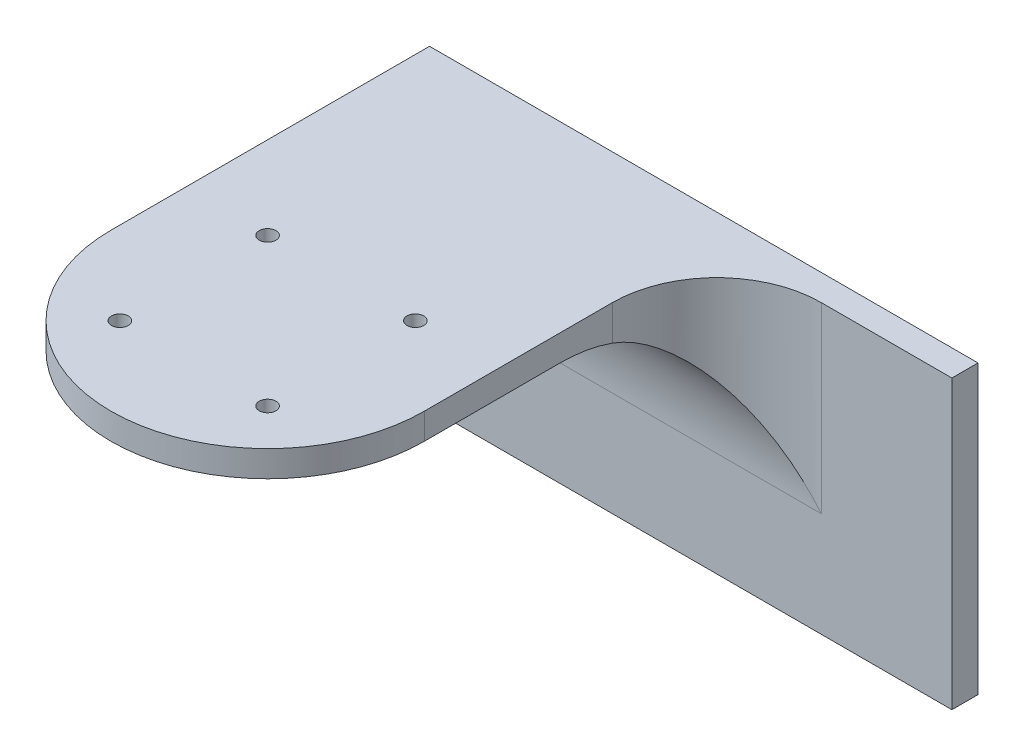
SolidWorks part; units mm, degrees
ref_plane "Front Plane" through (0, 0, 0) normal (0, 0, 1) x (1, 0, 0)
ref_plane "Top Plane" through (0, 0, 0) normal (0, 1, 0) x (1, 0, 0)
ref_plane "Right Plane" through (0, 0, 0) normal (1, 0, 0) x (0, 0, -1)
sketch "Sketch1" plane through (0, 0, 0) normal (0, 1, 0) x (1, 0, 0)
  line L0 (0, 0) -> (-21.2132, 21.2132) construction
  line L1 (0, 0) -> (0, 30) construction
  circle A0 centre (0, 0) radius 30
  circle A1 centre (14.1421, 14.1421) radius 1.6
  circle A2 centre (-14.1421, 14.1421) radius 1.6
  circle A3 centre (-14.1421, -14.1421) radius 1.6
  circle A4 centre (14.1421, -14.1421) radius 1.6
  dimension "D1" = 60
  dimension "D2" = 3.2
  dimension "D4" = 20
  dimension "D3" = 45
  dimension "D5" = 20
extrude "Boss-Extrude1" add sketch "Sketch1" along normal blind 5
sketch "Sketch2" plane through (0, 0, 0) normal (0, -1, 0) x (1, 0, 0)
  line L1 (-30, -61) -> (30, -61)
  line L3 (-30, 0) -> (-30, -61)
  line L4 (30, 0) -> (30, -61)
  circle A0 centre (0, 0) radius 30 construction
  arc A2 (-30, 0) -> (30, 0) centre (0, 0) ccw
  dimension "D1" = 61
extrude "Boss-Extrude2" add sketch "Sketch2" against normal blind 5
sketch "Sketch3" plane through (0, 0, 0) normal (0, -1, 0) x (1, 0, 0)
  line L0 (30, -61) -> (30, 0) construction
  line L1 (-30, -61) -> (30, -61)
  line L2 (-30, -61) -> (-30, -56)
  line L3 (-30, -56) -> (30, -56)
  line L4 (30, -61) -> (30, -56)
  dimension "D1" = 5
extrude "Boss-Extrude3" add sketch "Sketch3" along normal blind 50
fillet "Fillet1" radius 30 1 edges at (0, 0, -56)
sketch "Sketch4" plane through (30, 0, 0) normal (1, 0, 0) x (0, 0, -1)
  line L1 (56, -50) -> (61, -50)
  line L2 (56, -50) -> (56, 5)
  line L3 (56, 5) -> (61, 5)
  line L4 (61, -50) -> (61, 5)
extrude "Boss-Extrude4" add sketch "Sketch4" along normal blind 45
fillet "Fillet2" radius 20 1 edges at (30, -12.5, -56)
